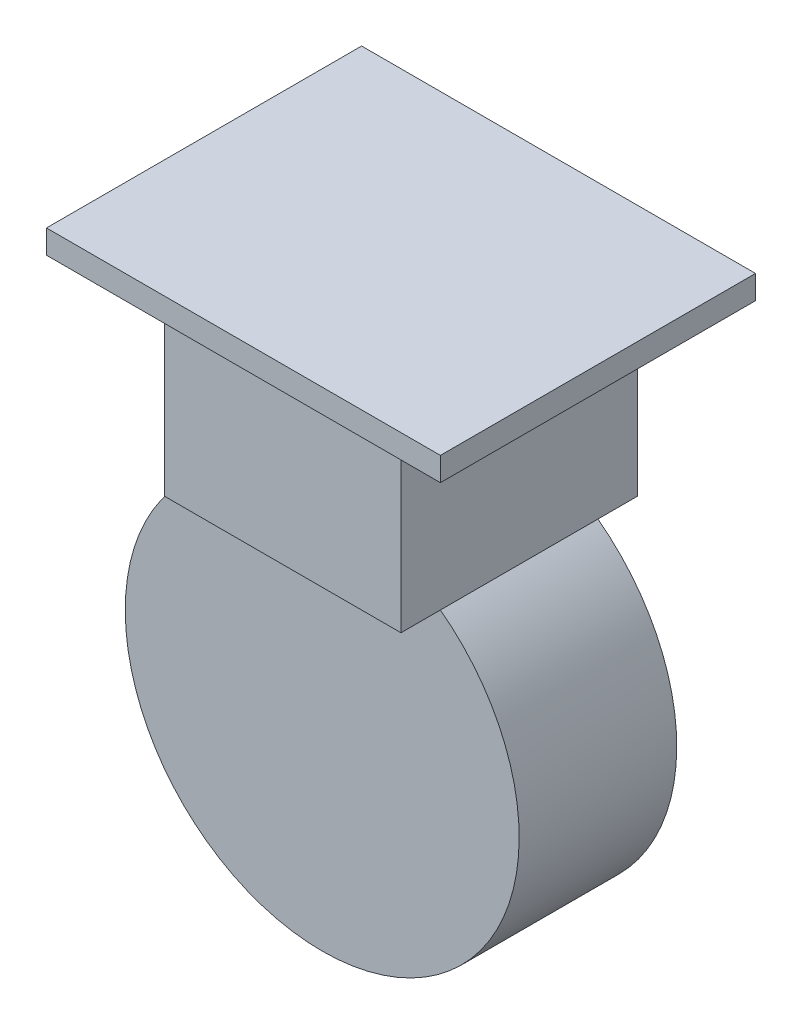
SolidWorks part; units mm, degrees
ref_plane "Front Plane" through (0, 0, 0) normal (0, 0, 1) x (1, 0, 0)
ref_plane "Top Plane" through (0, 0, 0) normal (0, 1, 0) x (1, 0, 0)
ref_plane "Right Plane" through (0, 0, 0) normal (1, 0, 0) x (0, 0, -1)
sketch "SK_CasterWheel" plane through (0, 0, 0) normal (0, 1, 0) x (1, 0, 0)
  line L0 (0, 10) -> (25, 10)
  line L1 (25, 10) -> (25, -10)
  line L2 (25, -10) -> (0, -10)
  line L3 (0, -10) -> (0, 10)
  line L4 (0, 15) -> (0, -15) construction
revolve "CasterWheel" add sketch "SK_CasterWheel" angle 360 about L4
sketch "SK_Fork" plane through (0, 0, 0) normal (0, 0, 1) x (1, 0, 0)
  line L0 (-15, 20) -> (15, 20)
  line L1 (15, 20) -> (15, 44)
  line L2 (15, 44) -> (-15, 44)
  line L3 (-15, 44) -> (-15, 20)
extrude "Fork" add sketch "SK_Fork" along normal mid plane 30
sketch "SK_TopPlate" plane through (0, 0, 0) normal (0, 0, 1) x (1, 0, 0)
  line L0 (-25, 44) -> (25, 44)
  line L1 (25, 44) -> (25, 47)
  line L2 (25, 47) -> (-25, 47)
  line L3 (-25, 47) -> (-25, 44)
extrude "TopPlate" add sketch "SK_TopPlate" along normal mid plane 40
